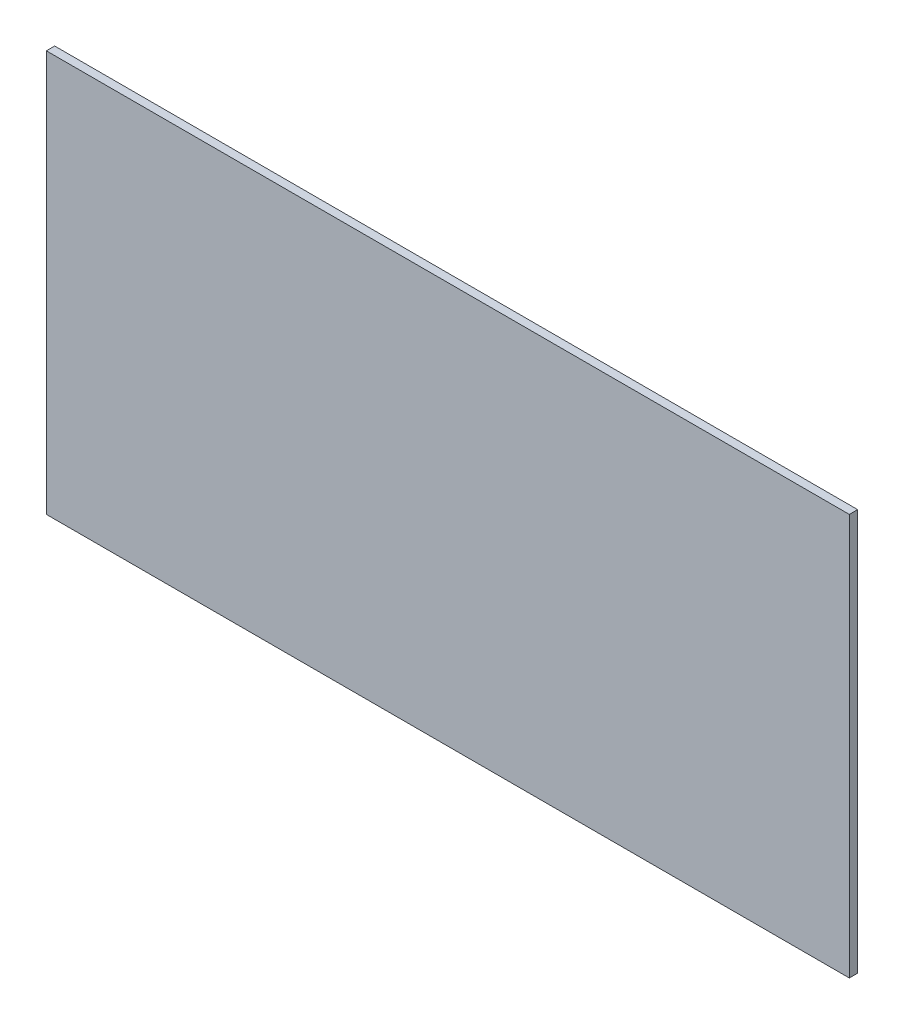
SolidWorks part; units mm, degrees
ref_plane "Front Plane" through (0, 0, 0) normal (0, 0, 1) x (1, 0, 0)
ref_plane "Top Plane" through (0, 0, 0) normal (0, 1, 0) x (1, 0, 0)
ref_plane "Right Plane" through (0, 0, 0) normal (1, 0, 0) x (0, 0, -1)
sketch "Sketch1" plane through (0, 0, 0) normal (0, 0, 1) x (1, 0, 0)
  line L1 (-304, -152) -> (304, -152)
  line L2 (-304, -152) -> (-304, 152)
  line L3 (-304, 152) -> (304, 152)
  line L4 (304, -152) -> (304, 152)
  line L5 (-304, -152) -> (304, 152) construction
  line L6 (-304, 152) -> (304, -152) construction
  point P0 (0, 0)
  dimension "D1" = 608
  dimension "D2" = 304
extrude "Boss-Extrude1" add sketch "Sketch1" along normal blind 6.3
